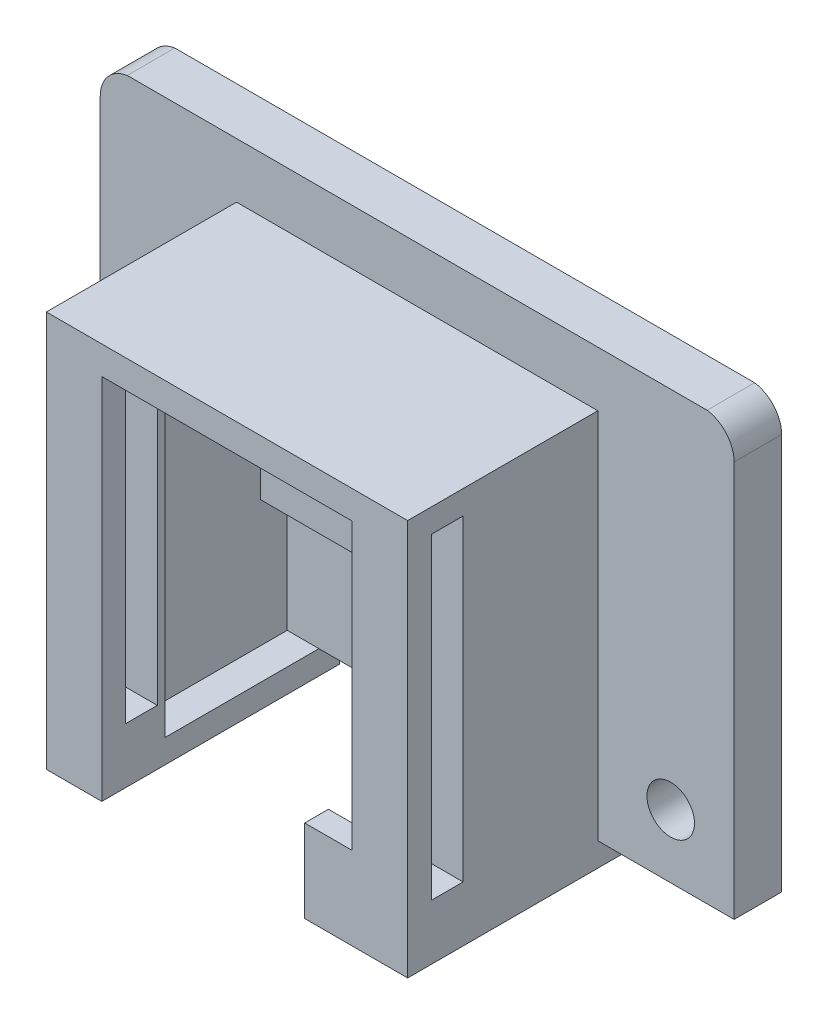
SolidWorks part; units mm, degrees
ref_plane "Alzado" through (0, 0, 0) normal (0, 0, 1) x (1, 0, 0)
ref_plane "Planta" through (0, 0, 0) normal (0, 1, 0) x (1, 0, 0)
ref_plane "Vista lateral" through (0, 0, 0) normal (1, 0, 0) x (0, 0, -1)
sketch "Croquis1" plane through (0, 0, 0) normal (0, 0, 1) x (1, 0, 0)
  line L2 (-75.3066, 17.9596) -> (-75.3066, -7.0404)
  line L3 (-75.3066, -7.0404) -> (-35.3066, -7.0404)
  line L4 (-35.3066, 17.9596) -> (-35.3066, -7.0404)
  line L6 (-55.3066, 22.682) -> (-35.3066, 22.682) construction
  line L8 (-73.6033, 19.9375) -> (-37.0099, 19.9375)
  circle A0 centre (-71.3066, -3.0404) radius 1.5
  circle A1 centre (-39.3066, -3.0404) radius 1.5
  arc A2 (-37.0099, 19.9375) -> (-35.3066, 17.9596) centre (-37.3066, 17.9596) cw
  arc A4 (-73.6033, 19.9375) -> (-75.3066, 17.9596) centre (-73.3066, 17.9596) ccw
  point P17 (-75.3066, 19.682)
  dimension "D3" = 2
  dimension "D4" = 32
  dimension "D5" = 3
  dimension "D6" = 3
  dimension "D1" = 4
  dimension "D2" = 3
  dimension "D7" = 4
  dimension "D8" = 4
  dimension "D9" = 25
extrude "Saliente-Extruir1" add sketch "Croquis1" along normal blind 3
sketch "Croquis2" plane through (0, 0, 3) normal (0, 0, 1) x (1, 0, 0)
  line L0 (-75.3066, -7.0404) -> (-35.3066, -7.0404) construction
  line L1 (-66.7066, -7.0404) -> (-65.2066, -7.0404)
  line L2 (-66.7066, -7.0404) -> (-66.7066, 16.4596)
  line L3 (-66.7066, 16.4596) -> (-43.9066, 16.4596)
  line L4 (-43.9066, -7.0404) -> (-43.9066, 16.4596)
  line L5 (-45.4066, -7.0404) -> (-43.9066, -7.0404)
  line L6 (-65.2066, 14.9596) -> (-45.4066, 14.9596)
  line L7 (-65.2066, 14.9596) -> (-65.2066, -7.0404)
  line L9 (-45.4066, 14.9596) -> (-45.4066, -7.0404)
  dimension "D1" = 22.8
  dimension "D3" = 23.5
  dimension "D4" = 1.5
  dimension "D5" = 1.5
  dimension "D6" = 1.5
extrude "Saliente-Extruir2" add sketch "Croquis2" along normal blind 8
sketch "Croquis3" plane through (0, -7.0404, 0) normal (0, -1, 0) x (1, 0, 0)
  line L1 (-65.2066, 3) -> (-52.2066, 3)
  line L2 (-65.2066, 3) -> (-65.2066, 1.3)
  line L3 (-65.2066, 1.3) -> (-52.2066, 1.3)
  line L4 (-52.2066, 3) -> (-52.2066, 1.3)
  dimension "D1" = 13
  dimension "D2" = 1.7
extrude "Cortar-Extruir1" cut sketch "Croquis3" against normal blind 8
sketch "Croquis5" plane through (0, -7.0404, 0) normal (0, -1, 0) x (1, 0, 0)
  line L0 (-75.3066, 0) -> (-35.3066, 0) construction
  line L1 (-66.7066, 11) -> (-63.2066, 11)
  line L2 (-66.7066, 11) -> (-66.7066, 0)
  line L3 (-66.7066, 0) -> (-63.2066, 0)
  line L4 (-63.2066, 11) -> (-63.2066, 0)
  line L5 (-45.4066, 11) -> (-45.4066, 3) construction
  line L6 (-43.9066, 11) -> (-50.4066, 11)
  line L7 (-43.9066, 11) -> (-43.9066, 0)
  line L8 (-43.9066, 0) -> (-50.4066, 0)
  line L9 (-50.4066, 11) -> (-50.4066, 0)
  line L10 (-65.2066, 11) -> (-65.2066, 1.3) construction
  dimension "D1" = 5
  dimension "D2" = 2
extrude "Saliente-Extruir3" add sketch "Croquis5" along normal blind 1.5
sketch "Croquis6" plane through (0, 0, 11) normal (0, 0, 1) x (1, 0, 0)
  line L0 (-63.2066, -7.0404) -> (-63.2066, -8.5404)
  line L1 (-63.2066, -8.5404) -> (-66.7066, -8.5404)
  line L2 (-66.7066, -8.5404) -> (-66.7066, 16.4596)
  line L3 (-66.7066, 16.4596) -> (-43.9066, 16.4596)
  line L4 (-43.9066, 16.4596) -> (-43.9066, -8.5404)
  line L5 (-43.9066, -8.5404) -> (-50.4066, -8.5404)
  line L6 (-50.4066, -8.5404) -> (-50.4066, -3.318)
  line L7 (-50.4066, -3.318) -> (-47.4066, -3.318)
  line L8 (-47.4066, -3.318) -> (-47.4066, 14.682)
  line L9 (-47.4066, 14.682) -> (-63.2066, 14.682)
  line L10 (-63.2066, 14.682) -> (-63.2066, -7.0404)
  dimension "D1" = 15.8
extrude "Saliente-Extruir4" add sketch "Croquis6" along normal blind 4
sketch "Croquis11" plane through (-66.7066, 0, 0) normal (-1, 0, 0) x (0, 0, 1)
  line L0 (15, 16.4596) -> (15, -8.5404) construction
  line L1 (13.5, 14.9596) -> (11.5, 14.9596)
  line L2 (13.5, 14.9596) -> (13.5, -5.0404)
  line L3 (13.5, -5.0404) -> (11.5, -5.0404)
  line L4 (11.5, 14.9596) -> (11.5, -5.0404)
  line L5 (15, 16.4596) -> (3, 16.4596) construction
  dimension "D1" = 1.5
  dimension "D2" = 2
  dimension "D3" = 20
  dimension "D4" = 1.5
extrude "Cortar-Extruir2" cut sketch "Croquis11" against normal up to vertex
